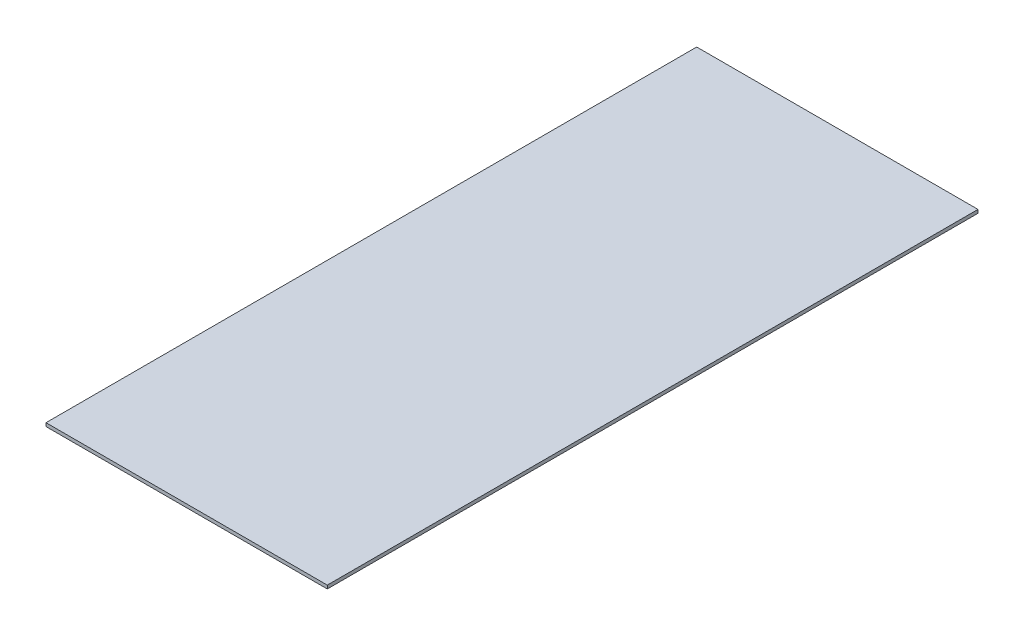
SolidWorks part; units mm, degrees
ref_plane "Front Plane" through (0, 0, 0) normal (0, 0, 1) x (1, 0, 0)
ref_plane "Top Plane" through (0, 0, 0) normal (0, 1, 0) x (1, 0, 0)
ref_plane "Right Plane" through (0, 0, 0) normal (1, 0, 0) x (0, 0, -1)
sketch "Sketch1" plane through (0, 0, 0) normal (0, 1, 0) x (1, 0, 0)
  line L1 (-527.05, -1219.2) -> (527.05, -1219.2)
  line L2 (-527.05, -1219.2) -> (-527.05, 1219.2)
  line L3 (-527.05, 1219.2) -> (527.05, 1219.2)
  line L4 (527.05, -1219.2) -> (527.05, 1219.2)
  line L5 (-527.05, -1219.2) -> (527.05, 1219.2) construction
  line L6 (-527.05, 1219.2) -> (527.05, -1219.2) construction
  point P0 (0, 0)
  dimension "D1" = 2438.4
  dimension "D2" = 1054.1
extrude "Boss-Extrude1" add sketch "Sketch1" along normal blind 12.7
